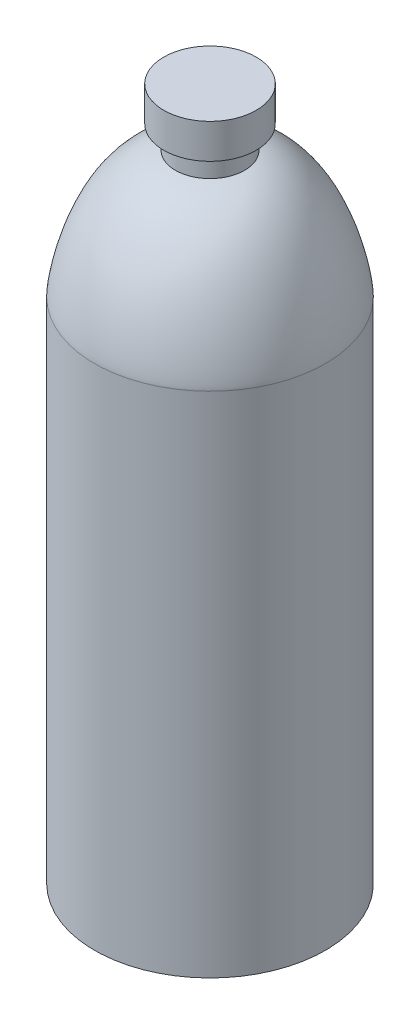
SolidWorks part; units mm, degrees
ref_plane "Front Plane" through (0, 0, 0) normal (0, 0, 1) x (1, 0, 0)
ref_plane "Top Plane" through (0, 0, 0) normal (0, 1, 0) x (1, 0, 0)
ref_plane "Right Plane" through (0, 0, 0) normal (1, 0, 0) x (0, 0, -1)
sketch "Sketch1" plane through (0, 0, 0) normal (1, 0, 0) x (0, 0, -1)
  line L0 (0, -95.25) -> (0, 95.25) construction
  line L1 (0, 95.25) -> (12.7, 95.25)
  line L2 (12.7, 95.25) -> (12.7, 85.725)
  line L3 (12.7, 85.725) -> (9.525, 85.725)
  line L4 (9.525, 85.725) -> (9.525, 79.375)
  line L5 (31.75, 44.45) -> (31.75, -95.25)
  line L6 (31.75, -95.25) -> (0, -95.25)
  line L7 (0, -95.25) -> (0, 95.25)
  spline S0 degree 3 poles (9.525, 79.375) (27.5233, 75.4748) (31.9, 46.8648) (31.75, 44.45) knots 0 0 0 0 1 1 1 1
  dimension "D7" = 139.7
  dimension "D1" = 190.5
  dimension "D2" = 25.4
  dimension "D3" = 19.05
  dimension "D4" = 63.5
  dimension "D5" = 9.525
  dimension "D6" = 15.875
revolve "Revolve1" add sketch "Sketch1" angle 360 about L0
